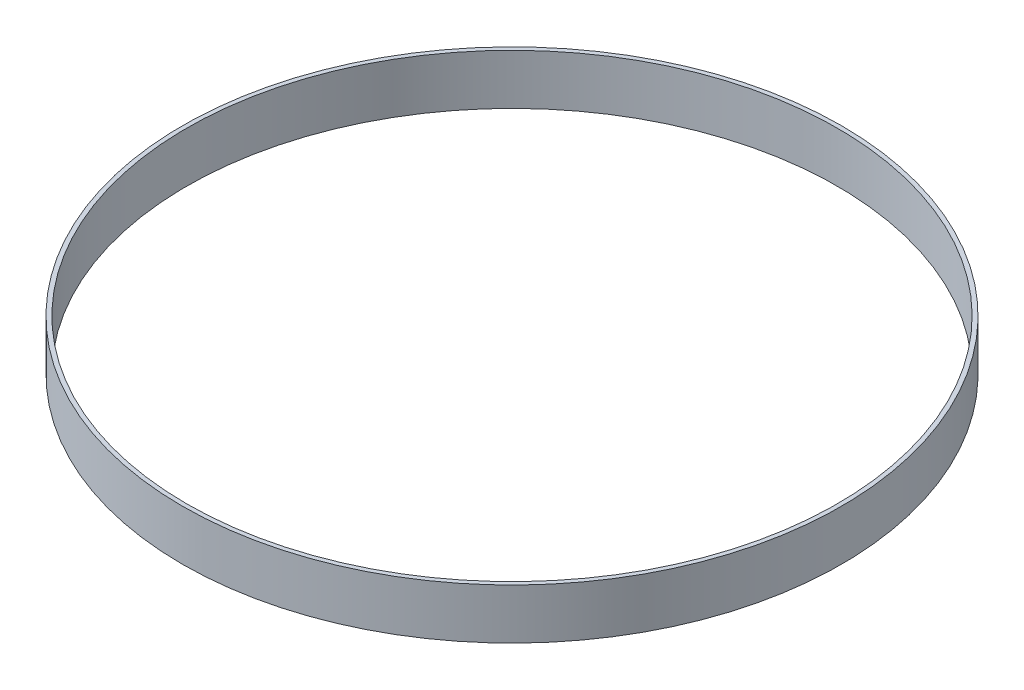
SolidWorks part; units mm, degrees
ref_plane "Front Plane" through (0, 0, 0) normal (0, 0, 1) x (1, 0, 0)
ref_plane "Top Plane" through (0, 0, 0) normal (0, 1, 0) x (1, 0, 0)
ref_plane "Right Plane" through (0, 0, 0) normal (1, 0, 0) x (0, 0, -1)
sketch "Sketch1" plane through (0, 0, 0) normal (0, 1, 0) x (1, 0, 0)
  circle A0 centre (0, 0) radius 39.3
  circle A1 centre (0, 0) radius 38.8
  dimension "D1" = 78.6
  dimension "D2" = 0.5
extrude "Boss-Extrude1" add sketch "Sketch1" along normal blind 6 contours A1
